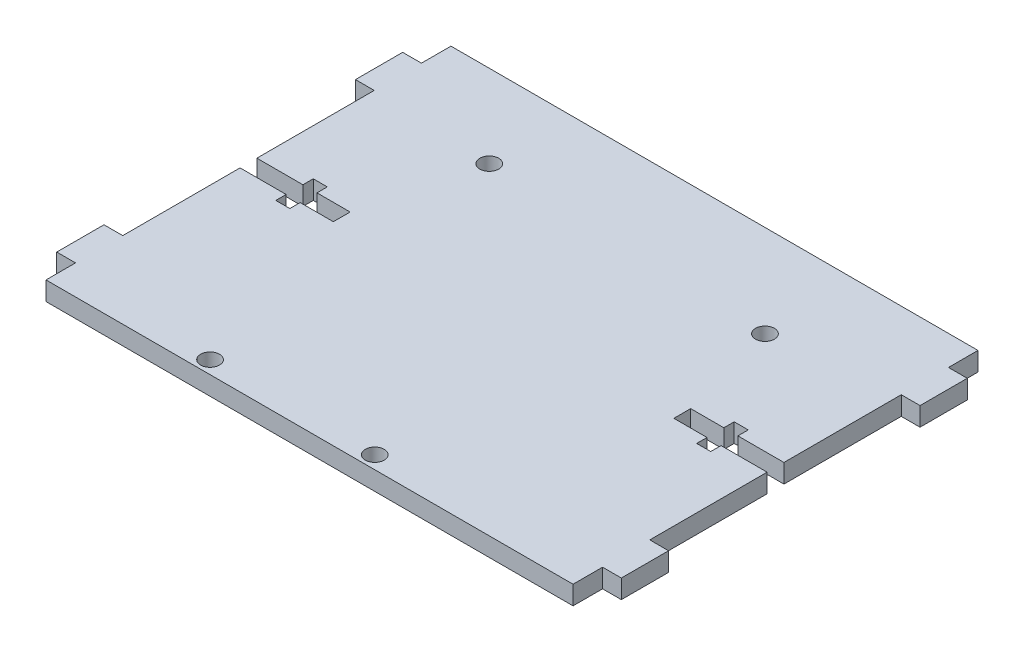
SolidWorks part; units mm, degrees
ref_plane "Front Plane" through (0, 0, 0) normal (0, 0, 1) x (1, 0, 0)
ref_plane "Top Plane" through (0, 0, 0) normal (0, 1, 0) x (1, 0, 0)
ref_plane "Right Plane" through (0, 0, 0) normal (1, 0, 0) x (0, 0, -1)
sketch "Sketch1" plane through (0, 0, 0) normal (0, 1, 0) x (1, 0, 0)
  line L1 (44.6419, 17.4753) -> (-44.6419, 17.4753)
  line L3 (-44.6419, -51.1247) -> (44.6419, -51.1247)
  line L8 (0, 17.4753) -> (0, 0) construction
  line L9 (0, 0) -> (0, -51.1247) construction
  line L16 (44.6419, 17.4753) -> (44.6419, 12.4753)
  line L17 (-44.6419, 17.4753) -> (-44.6419, 12.4753)
  line L18 (44.6419, 12.4753) -> (47.8219, 12.4753)
  line L19 (-44.6419, 12.4753) -> (-47.8219, 12.4753)
  line L20 (47.8219, 12.4753) -> (47.8219, 4.4753)
  line L21 (47.8219, 4.4753) -> (44.6419, 4.4753)
  line L22 (44.6419, 4.4753) -> (44.6419, -38.1247)
  line L23 (44.6419, -38.1247) -> (47.8219, -38.1247)
  line L24 (47.8219, -38.1247) -> (47.8219, -46.1247)
  line L25 (47.8219, -46.1247) -> (44.6419, -46.1247)
  line L26 (44.6419, -46.1247) -> (44.6419, -51.1247)
  line L27 (47.8219, 12.4753) -> (47.8219, 4.4753)
  line L28 (47.8219, -38.1247) -> (47.8219, -46.1247)
  line L34 (-47.8219, 12.4753) -> (-47.8219, 4.4753)
  line L36 (-47.8219, 4.4753) -> (-44.6419, 4.4753)
  line L37 (-44.6419, 4.4753) -> (-44.6419, -38.1247)
  line L38 (-44.6419, -38.1247) -> (-47.8219, -38.1247)
  line L39 (-47.8219, -38.1247) -> (-47.8219, -46.1247)
  line L40 (-47.8219, -46.1247) -> (-44.6419, -46.1247)
  line L41 (-44.6419, -46.1247) -> (-44.6419, -51.1247)
  circle A0 centre (24.15, 1.8753) radius 1.6 construction
  circle A1 centre (8.85, -48.9247) radius 1.6 construction
  circle A2 centre (-19.05, -48.9247) radius 1.6 construction
  circle A3 centre (-24.15, 3.4753) radius 1.6 construction
  circle A4 centre (24.15, 1.8753) radius 1.6
  circle A5 centre (8.85, -48.9247) radius 1.6
  circle A6 centre (-19.05, -48.9247) radius 1.6
  circle A7 centre (-24.15, 3.4753) radius 1.6
  dimension "D1" = 68.6
  dimension "D2" = 89.2838
  dimension "D3" = 3.18
extrude "Boss-Extrude1" add sketch "Sketch1" along normal blind 3.18
sketch "Sketch2" plane through (0, 3.18, 0) normal (0, 1, 0) x (1, 0, 0)
  line L17 (-44.6419, 4.4753) -> (-44.6419, -38.1247) construction
  line L18 (-44.6419, -15.3997) -> (-36.8419, -15.3997)
  line L19 (-36.8419, -15.3997) -> (-36.8419, -13.6497)
  line L20 (-36.8419, -13.6497) -> (-34.4619, -13.6497)
  line L21 (-34.4619, -13.6497) -> (-34.4619, -15.3997)
  line L22 (-34.4619, -15.3997) -> (-28.8419, -15.3997)
  line L23 (-28.8419, -15.3997) -> (-28.8419, -18.2497)
  line L24 (-28.8419, -18.2497) -> (-34.4619, -18.2497)
  line L25 (-34.4619, -18.2497) -> (-34.4619, -19.9997)
  line L26 (-34.4619, -19.9997) -> (-36.8419, -19.9997)
  line L27 (-36.8419, -19.9997) -> (-36.8419, -18.2497)
  line L28 (-36.8419, -18.2497) -> (-44.6419, -18.2497)
  line L29 (-44.6419, -18.2497) -> (-44.6419, -15.3997)
  line L30 (-44.6419, -38.1247) -> (-47.8219, -38.1247) construction
  dimension "D1" = 15.8
  dimension "D2" = 2.85
  dimension "D3" = 2.38
  dimension "D4" = 7.8
  dimension "D5" = 19.875
  dimension "D6" = 6.35
extrude "Cut-Extrude1" cut sketch "Sketch2" against normal through all
mirror "Mirror1" about plane through (0, 0, 0) normal (1, 0, 0) of "Cut-Extrude1"
